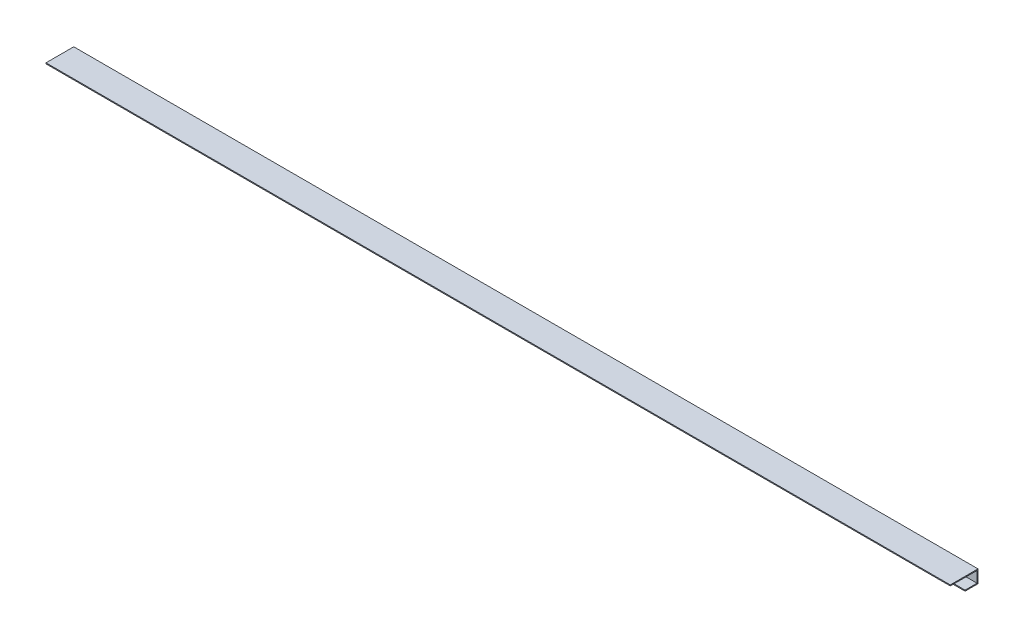
SolidWorks part; units mm, degrees
ref_plane "Front Plane" through (0, 0, 0) normal (0, 0, 1) x (1, 0, 0)
ref_plane "Top Plane" through (0, 0, 0) normal (0, 1, 0) x (1, 0, 0)
ref_plane "Right Plane" through (0, 0, 0) normal (1, 0, 0) x (0, 0, -1)
sketch "Sketch1" plane through (0, 0, 0) normal (1, 0, 0) x (0, 0, -1)
  line L0 (0, 0) -> (58, 0)
  line L1 (58, 0) -> (58, -27)
  line L2 (58, -27) -> (31, -27)
  line L3 (0, -2) -> (56, -2)
  line L4 (56, -2) -> (56, -25)
  line L5 (56, -25) -> (31, -25)
  line L6 (0, 0) -> (0, -2)
  line L7 (31, -25) -> (31, -27)
  dimension "D1" = 2
  dimension "D2" = 58
  dimension "D3" = 27
  dimension "D4" = 27
extrude "Boss-Extrude1" add sketch "Sketch1" along normal blind 1890
equation "\"door_base_short7_BR_Single_height\"=1890.0"
equation "\"D1@Boss-Extrude1\"=\"door_base_short7_BR_Single_height\""
equation "\"CarBeamWidth\"=700.0"
equation "\"WheelWidth\"=650.0"
equation "\"Wheel_FrontBoxDistance\"=1390.0"
equation "\"boxLength\"=5100.0"
equation "\"boxWidth\"=1930.0"
equation "\"MetalSheet_3mm_length\"=5030.0"
equation "\"MetalSheet_3mm_width\"=1923.0"
equation "\"MetalSheet_3mm_FloorCut_L_length\"=1764.0"
equation "\"MetalSheet_3mm_FloorCut_L_disdance\"=1665.0"
equation "\"MetalSheet_3mm_FloorCut_R_length\"=1764.0"
equation "\"MetalSheet_3mm_FloorCut_R_disdance\"=1665.0"
equation "\"indoorHeight\"=1940.0"
equation "\"indoorHeight_para\"=25.0"
equation "\"rearLightHeight_para\"=265.0"
equation "\"haveDoor_R\"=1"
equation "\"side_door_bottom_R_3mm_length\"=1934.0"
equation "\"side_door_bottom_R_3mm_toFrontDistance\"=1583.0"
equation "\"1Bar_Side_RF_3mm_length\"=1493.0"
equation "\"1Bar_Side_RB_3mm_length\"=1493.0"
equation "\"DoorSeparator_RF_3mm_withHinge_toFrontDistance\"=1673.0"
equation "\"DoorSeparator_RF_3mm_withHinge_exist\"=1"
equation "\"DoorSeparator_RB_3mm_withHinge_toFrontDistance\"=3427.0"
equation "\"DoorSeparator_RB_3mm_withHinge_exist\"=1"
equation "\"Door_R1_L_open_Single_toFrontDistance\"=2547.5"
equation "\"Door_R1_L_open_Single_exist\"=1"
equation "\"door_base_long7_R1_L_open_Single_height\"=1890.0"
equation "\"door_base_short7_R1_L_open_Single_height\"=1890.0"
equation "\"door_base_short7_R1_L_open_Single_width\"=864"
equation "\"Door_R1_R_open_Single_toFrontDistance\"=3422.0"
equation "\"Door_R1_R_open_Single_exist\"=1"
equation "\"door_base_long7_R1_R_open_Single_height\"=1890.0"
equation "\"door_base_short7_R1_R_open_Single_height\"=1890.0"
equation "\"door_base_short7_R1_R_open_Single_width\"=864"
equation "\"x\"=66.0"
equation "\"door_base_double_BL_height\"=1890.0"
equation "\"door_base_short7_BL_Single_height\"=1890.0"
equation "\"door_base_short7_BL_Single_width\"=864"
equation "\"door_base_long7_BR_Single_height\"=1890.0"
equation "\"door_base_short7_BR_Single_width\"=864"
equation "\"da\"=62.0"
equation "\"SquareTube_length\"=1923.0"
equation "\"channelSteel_length\"=5030.0"
equation "\"SquareTube_inFront_AvgDistance\"=285.0"
equation "\"SquareTube_inFront_TotalCount\"=5"
equation "\"SquareTube_inFront1_cutDepth50_R\"=0.5"
equation "\"SquareTube_inFront1_cutDepth50_L\"=0.5"
equation "\"SquareTube_inFront2_cutDepth50_R\"=0.5"
equation "\"SquareTube_inFront2_cutDepth50_L\"=0.5"
equation "\"SquareTube_inFront3_cutDepth50_R\"=0.5"
equation "\"SquareTube_inFront3_cutDepth50_L\"=0.5"
equation "\"SquareTube_inFront4_cutDepth50_R\"=0.5"
equation "\"SquareTube_inFront4_cutDepth50_L\"=0.5"
equation "\"SquareTube_inFront5_cutDepth50_R\"=50"
equation "\"SquareTube_inFront5_cutDepth50_L\"=50"
equation "\"SquareTube_inFront6_cutDepth50_R\"=50"
equation "\"SquareTube_inFront6_cutDepth50_L\"=50"
equation "\"SquareTube_inFront7_cutDepth50_R\"=50"
equation "\"SquareTube_inFront7_cutDepth50_L\"=50"
equation "\"SquareTube_inFront8_cutDepth50_R\"=50"
equation "\"SquareTube_inFront8_cutDepth50_L\"=50"
equation "\"SquareTube_inFront9_cutDepth50_R\"=50"
equation "\"SquareTube_inFront9_cutDepth50_L\"=50"
equation "\"SquareTube_inFront10_cutDepth50_R\"=50"
equation "\"SquareTube_inFront10_cutDepth50_L\"=50"
equation "\"SquareTube_inFront11_cutDepth50_R\"=50"
equation "\"SquareTube_inFront11_cutDepth50_L\"=50"
equation "\"SquareTube_inFront12_cutDepth50_R\"=50"
equation "\"SquareTube_inFront12_cutDepth50_L\"=50"
equation "\"SquareTube_inFront13_cutDepth50_R\"=50"
equation "\"SquareTube_inFront13_cutDepth50_L\"=50"
equation "\"SquareTube_inFront14_cutDepth50_R\"=50"
equation "\"SquareTube_inFront14_cutDepth50_L\"=50"
equation "\"SquareTube_inBack_AvgDistance\"=333.125"
equation "\"SquareTube_inBack_TotalCount\"=9"
equation "\"SquareTube_inBack1_cutDepth50_R\"=50"
equation "\"SquareTube_inBack1_cutDepth50_L\"=50"
equation "\"SquareTube_inBack2_cutDepth50_R\"=50"
equation "\"SquareTube_inBack2_cutDepth50_L\"=50"
equation "\"SquareTube_inBack3_cutDepth50_R\"=50"
equation "\"SquareTube_inBack3_cutDepth50_L\"=50"
equation "\"SquareTube_inBack4_cutDepth50_R\"=50"
equation "\"SquareTube_inBack4_cutDepth50_L\"=50"
equation "\"SquareTube_inBack5_cutDepth50_R\"=50"
equation "\"SquareTube_inBack5_cutDepth50_L\"=50"
equation "\"SquareTube_inBack6_cutDepth50_R\"=0.5"
equation "\"SquareTube_inBack6_cutDepth50_L\"=0.5"
equation "\"SquareTube_inBack7_cutDepth50_R\"=0.5"
equation "\"SquareTube_inBack7_cutDepth50_L\"=0.5"
equation "\"SquareTube_inBack8_cutDepth50_R\"=0.5"
equation "\"SquareTube_inBack8_cutDepth50_L\"=0.5"
